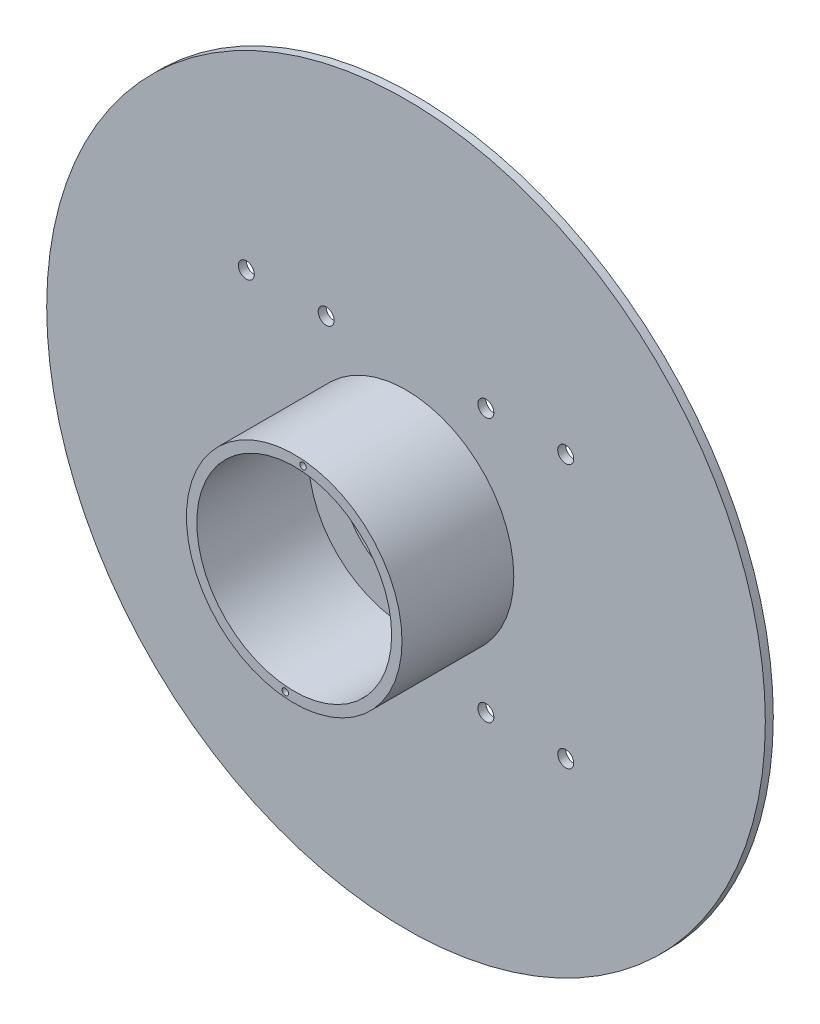
SolidWorks part; units mm, degrees
material "ABS"
ref_plane "前视基准面" through (0, 0, 0) normal (0, 0, 1) x (1, 0, 0)
ref_plane "上视基准面" through (0, 0, 0) normal (0, 1, 0) x (1, 0, 0)
ref_plane "右视基准面" through (0, 0, 0) normal (1, 0, 0) x (0, 0, -1)
sketch "草图1" plane through (0, 0, 0) normal (0, 0, 1) x (1, 0, 0)
  circle A0 centre (0, 0) radius 45
  dimension "D1" = 90
extrude "凸台-拉伸1" add sketch "草图1" along normal blind 1
sketch "草图2" plane through (0, 0, 1) normal (0, 0, 1) x (1, 0, 0)
  line L1 (-20, 16.5) -> (20, 16.5) construction
  line L2 (-20, 16.5) -> (-20, -16.5) construction
  line L3 (-20, -16.5) -> (20, -16.5) construction
  line L4 (20, 16.5) -> (20, -16.5) construction
  line L5 (-20, 16.5) -> (20, -16.5) construction
  line L6 (-20, -16.5) -> (20, 16.5) construction
  circle A0 centre (20, -16.5) radius 1
  circle A1 centre (20, 16.5) radius 1
  circle A2 centre (-20, 16.5) radius 1
  circle A3 centre (-20, -16.5) radius 1
  circle A4 centre (10, -16.5) radius 1
  circle A5 centre (10, 16.5) radius 1
  circle A6 centre (-10, 16.5) radius 1
  circle A7 centre (-10, -16.5) radius 1
  point P0 (0, 0)
  dimension "D3" = 2
  dimension "D4" = 2
  dimension "D5" = 2
  dimension "D6" = 2
  dimension "D7" = 10
  dimension "D8" = 10
  dimension "D9" = 2
  dimension "D10" = 2
  dimension "D11" = 2
  dimension "D12" = 2
  dimension "D13" = 10
  dimension "D14" = 10
  dimension "D1" = 40
  dimension "D2" = 33
extrude "切除-拉伸1" cut sketch "草图2" against normal through all
sketch "草图3" plane through (0, 0, 1) normal (0, 0, 1) x (1, 0, 0)
  circle A0 centre (0, 0) radius 12.2
  circle A1 centre (0, 0) radius 13.5
  dimension "D1" = 24.4
  dimension "D2" = 27
extrude "凸台-拉伸2" add sketch "草图3" along normal blind 6
sketch "草图4" plane through (0, 0, 1) normal (0, 0, 1) x (1, 0, 0)
  circle A0 centre (0, 0) radius 4
  dimension "D1" = 8
extrude "切除-拉伸2" cut sketch "草图4" against normal through all
sketch "草图5" plane through (0, 0, 1) normal (0, 0, 1) x (1, 0, 0)
  circle A0 centre (0, 0) radius 8
  dimension "D1" = 16
extrude "切除-拉伸3" cut sketch "草图5" against normal blind 10
sketch "草图6" plane through (0, 0, 7) normal (0, 0, 1) x (1, 0, 0)
  circle A0 centre (0, 0) radius 12.2
  circle A1 centre (0, 0) radius 13.5
extrude "凸台-拉伸3" add sketch "草图6" along normal blind 8
extrude "切除-拉伸4" cut sketch "草图7" against normal blind 2.8
sketch "草图7" plane through (65.7284, -2.3438, 15) normal (0, 0, 1) x (1, -0.0053, 0)
  circle A0 centre (-64.6987, 14.8012) radius 0.4
  circle A1 centre (-66.7813, -10.8143) radius 0.4
